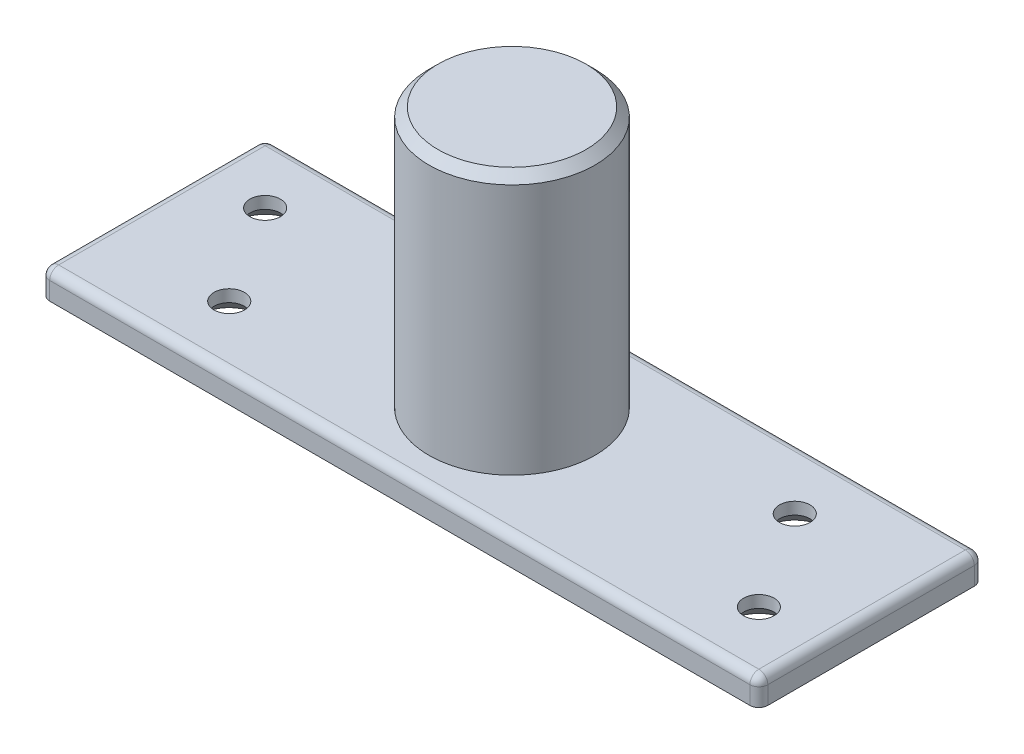
SolidWorks part; units mm, degrees
material "Aço cromo inoxidável"
ref_plane "Plano frontal" through (0, 0, 0) normal (0, 0, 1) x (1, 0, 0)
ref_plane "Plano superior" through (0, 0, 0) normal (0, 1, 0) x (1, 0, 0)
ref_plane "Plano direito" through (0, 0, 0) normal (1, 0, 0) x (0, 0, -1)
sketch "Esboço1" plane through (0, 0, 0) normal (0, 1, 0) x (1, 0, 0)
  line L1 (-39, -12.5) -> (39, -12.5)
  line L2 (-40, -11.5) -> (-40, 11.5)
  line L3 (-39, 12.5) -> (39, 12.5)
  line L4 (40, -11.5) -> (40, 11.5)
  line L5 (-40, -12.5) -> (40, 12.5) construction
  line L6 (-40, 12.5) -> (40, -12.5) construction
  arc A0 (39, -12.5) -> (40, -11.5) centre (39, -11.5) ccw
  arc A1 (-40, 11.5) -> (-39, 12.5) centre (-39, 11.5) cw
  arc A2 (-39, -12.5) -> (-40, -11.5) centre (-39, -11.5) cw
  arc A3 (39, 12.5) -> (40, 11.5) centre (39, 11.5) cw
  circle A4 centre (0, 0) radius 9.25
  point P0 (0, 0)
  dimension "D3" = 1
  dimension "D4" = 18.5
  dimension "D1" = 80
  dimension "D2" = 25
extrude "Ressalto-extrusão1" add sketch "Esboço1" along normal mid plane 3
sketch "Esboço3" plane through (0, -1.5, 0) normal (0, -1, 0) x (1, 0, 0)
  circle A0 centre (0, 0) radius 9.25 construction
  circle A1 centre (0, 0) radius 9.25
extrude "Ressalto-extrusão3" add sketch "Esboço3" against normal blind 32 separate body
shell "Casca1" thickness 3
chamfer "Chanfro1" distance 1 angle 45 1 edges at (0, 30.5, -9.25)
fillet "Filete1" radius 1 8 edges at (-39.7071, 1.5, 12.2071) (-40, 1.5, 0) (-39.7071, 1.5, -12.2071) (0, 1.5, -12.5) (39.7071, 1.5, -12.2071) (40, 1.5, 0) (39.7071, 1.5, 12.2071) (0, 1.5, 12.5)
chamfer "Chanfro2" distance 1 angle 45 2 edges at (0, -1.5, -6.25) (0, -1.5, -9.25)
sketch "Esboço4" plane through (0, -1.5, 0) normal (0, -1, 0) x (1, 0, 0)
  point P0 (-26, 5.5)
  point P1 (-33, -5.5)
  point P3 (26, -5.5)
  point P5 (33, 5.5)
  dimension "D1" = 26
  dimension "D2" = 33
  dimension "D3" = 26
  dimension "D4" = 33
  dimension "D5" = 5.5
  dimension "D6" = 5.5
hole_wizard "Escareado para SFHCS M31" positions "Esboço5" profile "Esboço6" countersink size "M3" standard "Ansi Metric" end condition through all
sketch "Esboço5" plane through (0, -1.5, 0) normal (0, -1, 0) x (-1, 0, 0)
  point P0 (-26, 5.5)
  point P3 (-33, -5.5)
  point P6 (26, -5.5)
  point P9 (33, 5.5)
sketch "Esboço6" plane through (26, -1.5, -5.5) normal (1, 0, 0) x (0, 0, -1)
  line L0 (0, 0) -> (0, 32)
  line L1 (0, 32) -> (1.7, 32)
  line L2 (1.7, 32) -> (1.7, 1.66)
  line L3 (1.7, 1.66) -> (3.36, 0)
  line L5 (3.36, 0) -> (0, 0)
  line L6 (-1.7, 1.66) -> (-3.36, 0) construction
  line L11 (0, -6.35) -> (0, 107.95) construction
  dimension "Thru Hole Dia." = 3.4
  dimension "Thru Hole Depth" = 32
  dimension "Near C'Sink Dia." = 6.72
  dimension "Near C'Sink Angle" = 90
